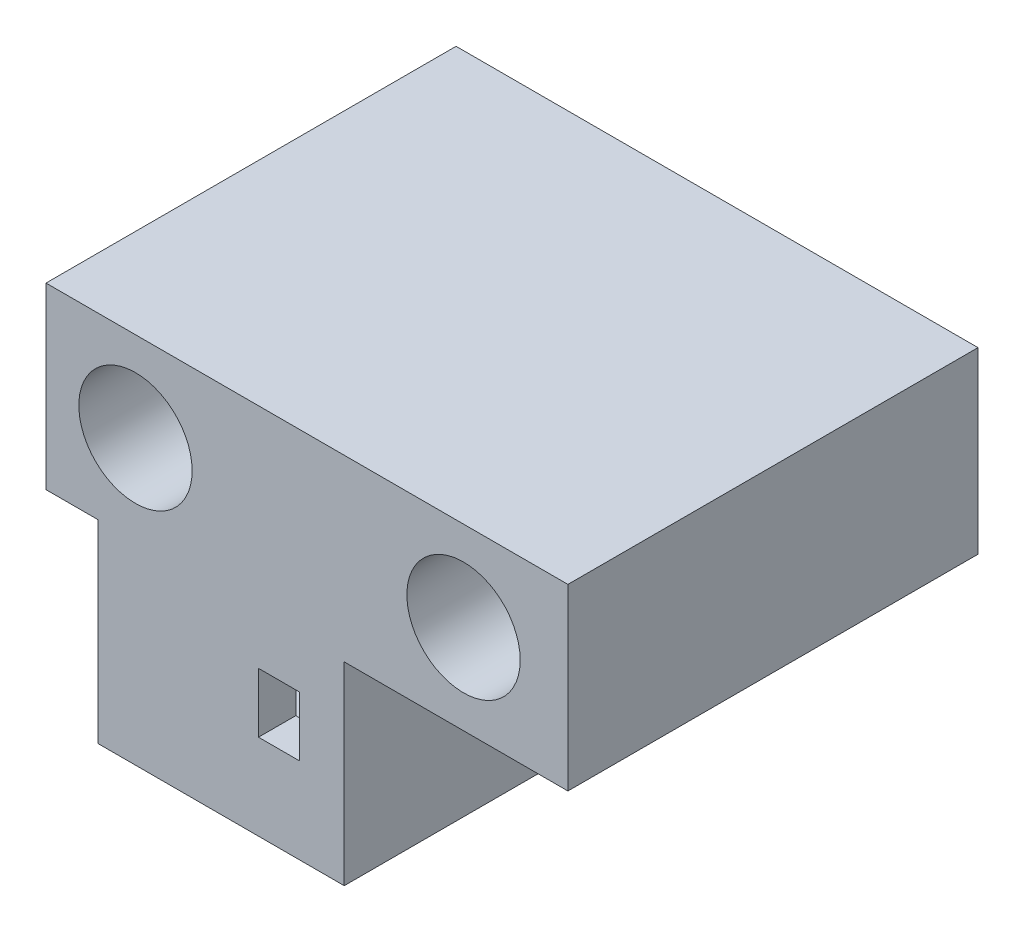
SolidWorks part; units mm, degrees
ref_plane "Plan de face" through (0, 0, 0) normal (0, 0, 1) x (1, 0, 0)
ref_plane "Plan de dessus" through (0, 0, 0) normal (0, 1, 0) x (1, 0, 0)
ref_plane "Plan de droite" through (0, 0, 0) normal (1, 0, 0) x (0, 0, -1)
sketch "Esquisse1" plane through (0, 0, 0) normal (0, 0, 1) x (1, 0, 0)
  line L1 (0, 0) -> (70, 0)
  line L2 (0, 0) -> (0, 24)
  line L3 (0, 24) -> (70, 24)
  line L4 (70, 0) -> (70, 24)
  dimension "D2" = 24
  dimension "D1" = 70
extrude "Boss.-Extru.1" add sketch "Esquisse1" along normal blind 55
sketch "Esquisse2" plane through (0, 0, 0) normal (0, 0, 1) x (1, 0, 0)
  line L0 (0, 24) -> (0, 0) construction
  line L2 (70, 24) -> (0, 24) construction
  circle A0 centre (56, 12) radius 7.6
  circle A1 centre (12, 12) radius 7.6
  dimension "D1" = 44
  dimension "D2" = 15.2
  dimension "D3" = 15.2
  dimension "D4" = 12
  dimension "D6" = 12
  dimension "D5" = 12
extrude "Enlèv. mat.-Extru.1" cut sketch "Esquisse2" along normal through all
sketch "Esquisse6" plane through (0, 0, 0) normal (0, -1, 0) x (1, 0, 0)
  line L0 (0, 0) -> (70, 0) construction
  line L1 (7, 0) -> (40, 0)
  line L2 (7, 0) -> (7, 5)
  line L3 (7, 5) -> (35, 5)
  line L4 (35, 5) -> (35, 50)
  line L5 (0, 55) -> (70, 55) construction
  line L6 (7, 55) -> (40, 55)
  line L7 (7, 55) -> (7, 50)
  line L8 (7, 50) -> (35, 50)
  line L9 (40, 0) -> (40, 55)
  line L10 (0, 55) -> (0, 0) construction
  dimension "D1" = 7
  dimension "D2" = 5
  dimension "D3" = 5
  dimension "D4" = 7
  dimension "D5" = 5
  dimension "D6" = 33
extrude "Boss.-Extru.3" add sketch "Esquisse6" along normal blind 21
sketch "Esquisse9" plane through (0, -21, 0) normal (0, -1, 0) x (1, 0, 0)
  line L1 (40, 55) -> (7, 55)
  line L2 (40, 55) -> (40, 0)
  line L3 (40, 0) -> (7, 0)
  line L4 (7, 55) -> (7, 0)
extrude "Boss.-Extru.4" add sketch "Esquisse9" along normal blind 5
sketch "Esquisse10" plane through (7, 0, 0) normal (-1, 0, 0) x (0, 0, 1)
  line L0 (5, 0) -> (0, 0) construction
  line L1 (55, 0) -> (50, 0) construction
  line L2 (50, -21) -> (50, 0) construction
  line L3 (0, -26) -> (0, 0) construction
  circle A0 centre (52.5, -16) radius 1.5
  circle A1 centre (52.5, -5) radius 1.5
  circle A2 centre (2.5, -16) radius 1.5
  circle A3 centre (2.5, -5) radius 1.5
  dimension "D1" = 3
  dimension "D2" = 3
  dimension "D3" = 3
  dimension "D4" = 3
  dimension "D5" = 16
  dimension "D6" = 5
  dimension "D7" = 5
  dimension "D8" = 16
  dimension "D9" = 2.5
  dimension "D10" = 2.5
  dimension "D11" = 2.5
  dimension "D12" = 2.5
extrude "Enlèv. mat.-Extru.4" cut sketch "Esquisse10" against normal blind 4
sketch "Esquisse11" plane through (0, 0, 55) normal (0, 0, 1) x (1, 0, 0)
  line L0 (40, -26) -> (40, 0) construction
  line L1 (28.5, -14.5) -> (34, -14.5)
  line L2 (28.5, -14.5) -> (28.5, -6.5)
  line L3 (28.5, -6.5) -> (34, -6.5)
  line L4 (34, -14.5) -> (34, -6.5)
  line L6 (40, -26) -> (7, -26) construction
  point P4 (34, -10.5)
  dimension "D1" = 6
  dimension "D2" = 11.5
  dimension "D3" = 8
  dimension "D4" = 5.5
extrude "Enlèv. mat.-Extru.5" cut sketch "Esquisse11" against normal blind 10
